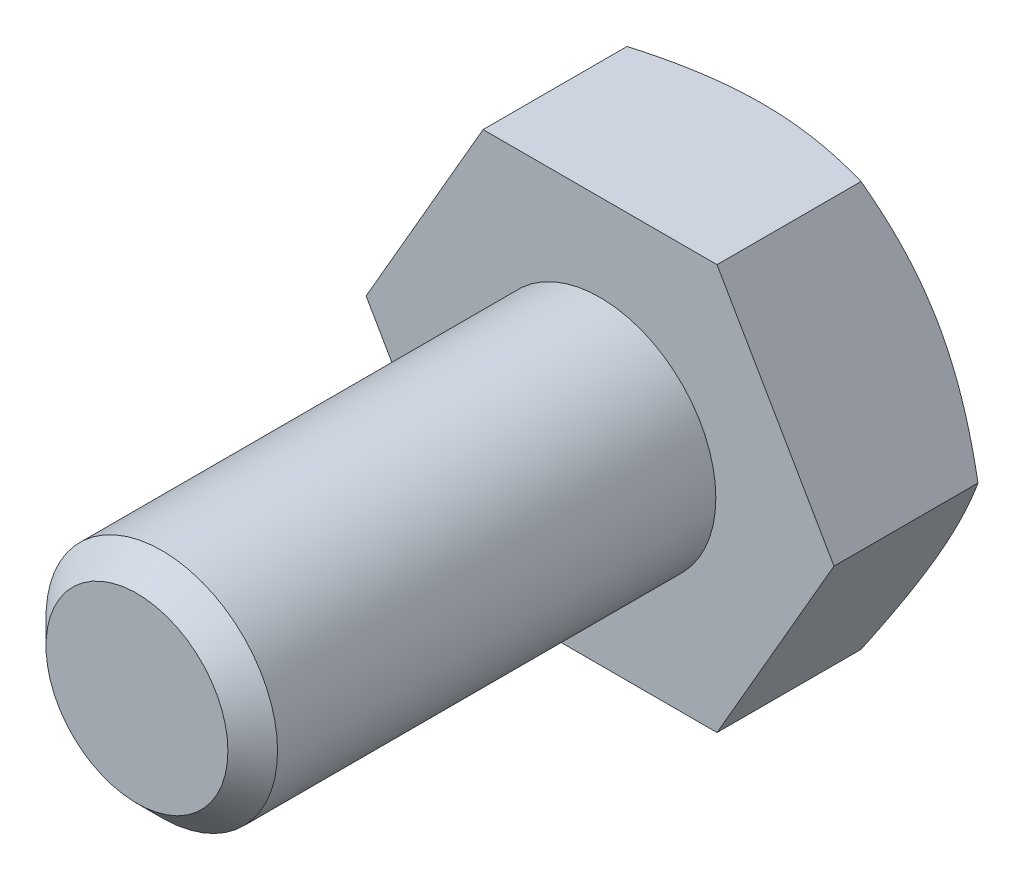
SolidWorks part; units mm, degrees
material "Plain Carbon Steel"
ref_plane "Front Plane" through (0, 0, 0) normal (0, 0, 1) x (1, 0, 0)
ref_plane "Top Plane" through (0, 0, 0) normal (0, 1, 0) x (1, 0, 0)
ref_plane "Right Plane" through (0, 0, 0) normal (1, 0, 0) x (0, 0, -1)
sketch "Sketch1" plane through (0, 0, 0) normal (0, 0, 1) x (1, 0, 0)
  line L1 (4.0415, 0) -> (2.0207, 3.5)
  line L2 (2.0207, 3.5) -> (-2.0207, 3.5)
  line L3 (-2.0207, 3.5) -> (-4.0415, 0)
  line L4 (-4.0415, 0) -> (-2.0207, -3.5)
  line L5 (-2.0207, -3.5) -> (2.0207, -3.5)
  line L6 (2.0207, -3.5) -> (4.0415, 0)
  circle A0 centre (0, 0) radius 3.5 construction
  dimension "D1" = 7
extrude "Extrude1" add sketch "Sketch1" along normal blind 2.8
sketch "Sketch2" plane through (0, 0, 2.8) normal (0, 0, 1) x (1, 0, 0)
  circle A0 centre (0, 0) radius 2
  dimension "D1" = 4
extrude "Extrude2" add sketch "Sketch2" along normal blind 8
cosmetic thread "Cosmetic Thread1" parameters "D2"=3.142
sketch "Sketch3" plane through (0, 0, 0) normal (1, 0, 0) x (0, 0, -1)
  line L0 (0, 3.5) -> (0, 103.5)
  line L1 (0, 103.5) -> (-57.735, 103.5)
  line L2 (-57.735, 103.5) -> (0, 3.5)
  line L3 (0, 0) -> (11.4679, 0) construction
  dimension "D1" = 30
  dimension "D2" = 100
revolve "Cut-Revolve1" cut sketch "Sketch3" angle 360 about L3
chamfer "Chamfer1" distance 0.429 angle 45 1 edges at (2, 0, 10.8)
